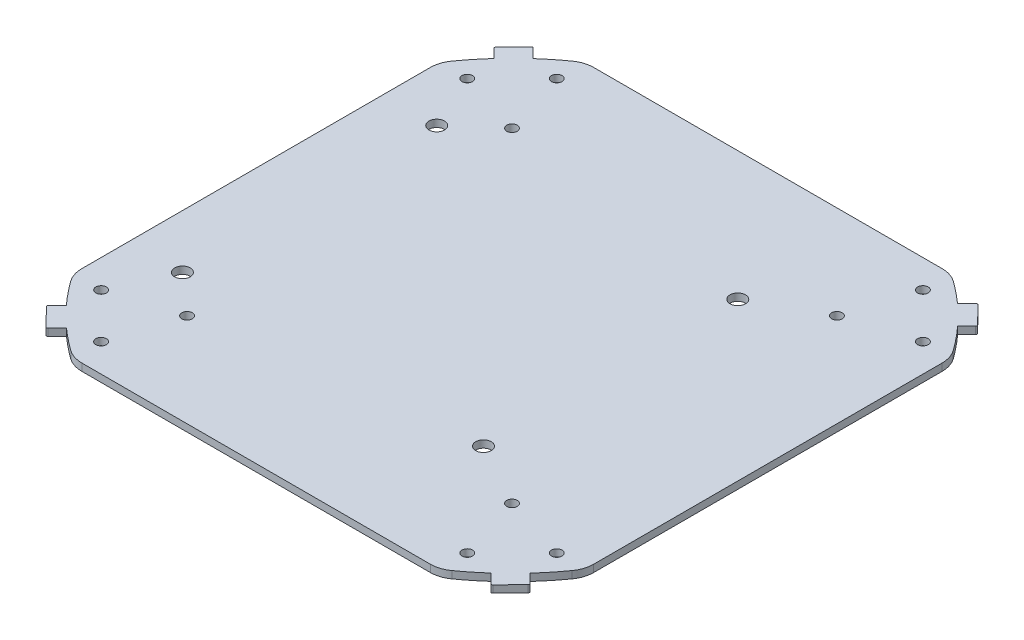
SolidWorks part; units mm, degrees
ref_plane "Front Plane" through (0, 0, 0) normal (0, 0, 1) x (1, 0, 0)
ref_plane "Top Plane" through (0, 0, 0) normal (0, 1, 0) x (1, 0, 0)
ref_plane "Right Plane" through (0, 0, 0) normal (1, 0, 0) x (0, 0, -1)
sketch "Sketch1" plane through (0, 0, 0) normal (0, 1, 0) x (1, 0, 0)
  line L0 (-1000, 0) -> (49000, 0) construction
  line L1 (0, -1000) -> (0, 49000) construction
  line L2 (707.1069, -707.1069) -> (-34648.2322, 34648.2322) construction
  line L3 (-707.1068, -707.1068) -> (34648.2323, 34648.2323) construction
  line L4 (716.0871, -698.1266) -> (0, 17.9605) construction
  line L5 (-698.1265, -716.087) -> (34657.2125, 34639.252) construction
  line L6 (698.1266, -716.0871) -> (-34657.2125, 34639.2519) construction
  line L7 (-716.087, -698.1265) -> (0, 17.9605) construction
  line L8 (-733.6258, -670.2105) -> (-31.7077, 31.7077) construction
  line L9 (733.9751, -670.5597) -> (22.7274, 40.6879) construction
  line L10 (39.5829, 36.115) -> (36.1358, 39.5583) construction
  line L11 (716.0871, -698.1266) -> (-34639.252, 34657.2125) construction
  line L12 (35.7817, 39.5534) -> (33.9856, 37.7573) construction
  line L13 (-716.087, -698.1265) -> (34639.252, 34657.2125) construction
  line L14 (39.5739, 35.7609) -> (37.7573, 33.9856) construction
  line L15 (39.5382, -36.1548) -> (36.0819, -39.6111) construction
  line L16 (39.5078, -35.8322) -> (37.7118, -34.0362) construction
  line L17 (-35.9968, -39.6764) -> (-39.3444, -36.2512) construction
  line L18 (-37.6038, -34.1555) -> (-39.3423, -35.894) construction
  line L19 (35.7129, -39.6171) -> (33.9376, -37.8006) construction
  line L20 (-35.6141, -39.7036) -> (-33.8181, -37.9075) construction
  line L21 (-39.7221, 35.8999) -> (-36.251, 39.2922) construction
  line L22 (-34.2033, 37.5603) -> (-35.8918, 39.2881) construction
  line L24 (-37.9528, 33.7672) -> (-39.7242, 35.5386) construction
  line L25 (-44.6575, -41.2092) -> (-46.396, -42.9477)
  line L26 (-43.0506, -46.7302) -> (-46.3981, -43.3049)
  line L27 (-42.6678, -46.7573) -> (-40.8718, -44.9612)
  line L28 (42.6678, -46.7573) -> (40.8718, -44.9612)
  line L29 (43.0506, -46.7302) -> (46.3981, -43.3049)
  line L30 (-39.4203, -35.9308) -> (-37.6038, -34.1555) [skipped]
  line L31 (-39.7488, 35.5633) -> (-37.9528, 33.7672) [skipped]
  line L32 (-35.9786, 39.3768) -> (-34.2033, 37.5603) [skipped]
  line L33 (44.6575, -41.2092) -> (46.396, -42.9477)
  line L35 (-44.6575, 41.2092) -> (-46.396, 42.9477)
  line L36 (-43.0506, 46.7302) -> (-46.3981, 43.3049)
  line L37 (-42.6678, 46.7573) -> (-40.8718, 44.9612)
  line L38 (44.6575, 41.2092) -> (46.396, 42.9477)
  line L39 (43.0506, 46.7302) -> (46.3981, 43.3049)
  line L40 (42.6678, 46.7573) -> (40.8718, 44.9612)
  line L43 (-33.5727, -49.3122) -> (33.5727, -49.3122)
  line L44 (49.3122, 33.5727) -> (49.3122, -33.5727)
  line L45 (33.5727, 49.3122) -> (-33.5727, 49.3122)
  line L46 (-49.3122, 33.5727) -> (-49.3122, -33.5727)
  arc A0 (-29.6486, 41.2505) -> (-34.2033, 37.5603) centre (0, 0) ccw construction
  arc A1 (-22.7274, 40.6879) -> (-29.6486, 41.2505) centre (-26.519, 36.8963) ccw construction
  arc A2 (-40.6879, 22.7274) -> (-41.2505, 29.6486) centre (-36.8963, 26.519) cw construction
  arc A3 (22.7274, 40.6879) -> (29.6486, 41.2505) centre (26.519, 36.8963) cw construction
  arc A4 (40.6879, 22.7274) -> (41.2505, 29.6486) centre (36.8963, 26.519) ccw construction
  arc A5 (40.6879, -22.7274) -> (41.2505, -29.6486) centre (36.8963, -26.519) cw construction
  arc A6 (22.7274, -40.6879) -> (29.6486, -41.2505) centre (26.519, -36.8963) ccw construction
  arc A7 (-22.7274, -40.6879) -> (-29.6486, -41.2505) centre (-26.519, -36.8963) cw construction
  arc A8 (-40.6879, -22.7274) -> (-41.2505, -29.6486) centre (-36.8963, -26.519) ccw construction
  arc A9 (-22.7274, 40.6879) -> (22.7274, 40.6879) centre (0, 66.2866) ccw construction
  arc A10 (40.6879, 22.7274) -> (40.6879, -22.7274) centre (66.2866, 0) ccw construction
  arc A11 (22.7274, -40.6879) -> (-22.7274, -40.6879) centre (0, -66.2866) ccw construction
  arc A12 (-40.6879, -22.7274) -> (-40.6879, 22.7274) centre (-66.2866, 0) ccw construction
  arc A13 (-29.6486, 41.2505) -> (-34.2033, 37.5603) centre (0, 0) ccw construction
  arc A14 (41.2505, 29.6486) -> (37.7573, 33.9856) centre (0, 0) ccw construction
  arc A15 (41.2505, 29.6486) -> (37.7573, 33.9856) centre (0, 0) ccw construction
  arc A16 (29.6486, -41.2505) -> (33.9376, -37.8006) centre (0, 0) ccw construction
  arc A17 (29.6486, -41.2505) -> (33.9376, -37.8006) centre (0, 0) ccw construction
  arc A18 (-41.2505, -29.6486) -> (-37.6038, -34.1555) centre (0, 0) ccw construction
  arc A19 (-41.2505, -29.6486) -> (-37.6038, -34.1555) centre (0, 0) ccw construction
  arc A20 (33.9856, 37.7573) -> (29.6486, 41.2505) centre (0, 0) ccw construction
  arc A21 (33.9856, 37.7573) -> (29.6486, 41.2505) centre (0, 0) ccw construction
  arc A22 (37.7118, -34.0362) -> (41.2505, -29.6486) centre (0, 0) ccw construction
  arc A23 (37.7118, -34.0362) -> (41.2505, -29.6486) centre (0, 0) ccw construction
  arc A24 (-33.8181, -37.9075) -> (-29.6486, -41.2505) centre (0, 0) ccw construction
  arc A25 (-33.8181, -37.9075) -> (-29.6486, -41.2505) centre (0, 0) ccw construction
  arc A26 (-37.9528, 33.7672) -> (-41.2505, 29.6486) centre (0, 0) ccw construction
  arc A27 (-37.9528, 33.7672) -> (-41.2505, 29.6486) centre (0, 0) ccw construction
  arc A28 (-35.6141, -39.7036) -> (-35.9968, -39.6764) centre (-35.7937, -39.5239) cw construction
  arc A29 (-39.3423, -35.894) -> (-39.3444, -36.2512) centre (-39.1627, -36.0736) ccw construction
  arc A30 (35.7129, -39.6171) -> (36.0819, -39.6111) centre (35.8945, -39.4396) ccw construction
  arc A31 (39.5078, -35.8322) -> (39.5382, -36.1548) centre (39.3282, -36.0118) cw construction
  arc A32 (39.5739, 35.7609) -> (39.5829, 36.115) centre (39.3964, 35.9426) ccw construction
  arc A33 (36.1358, 39.5583) -> (35.7817, 39.5534) centre (35.9613, 39.3738) ccw construction
  arc A34 (-39.7221, 35.8999) -> (-39.7242, 35.5386) centre (-39.5446, 35.7182) ccw construction
  arc A35 (-36.251, 39.2922) -> (-35.8918, 39.2881) centre (-36.0735, 39.1105) cw construction
  circle A36 centre (-28.2202, 36.8412) radius 1.016 construction
  circle A37 centre (-36.8412, 28.2202) radius 1.016 construction
  circle A38 centre (-24.2455, 24.2455) radius 1.016 construction
  circle A39 centre (28.2202, 36.8412) radius 1.016 construction
  circle A40 centre (36.8412, 28.2202) radius 1.016 construction
  circle A41 centre (24.2455, 24.2455) radius 1.016 construction
  circle A42 centre (36.8412, -28.2202) radius 1.016 construction
  circle A43 centre (28.2202, -36.8412) radius 1.016 construction
  circle A44 centre (24.2455, -24.2455) radius 1.016 construction
  circle A45 centre (-28.2202, -36.8412) radius 1.016 construction
  circle A46 centre (-36.8412, -28.2202) radius 1.016 construction
  circle A47 centre (-24.2455, -24.2455) radius 1.016 construction
  circle A48 centre (0, 0) radius 6.1441 construction
  arc A49 (-49.3122, -33.5727) -> (-48.3042, -36.7023) centre (-43.9501, -33.5727) ccw
  arc A50 (-48.3042, -36.7023) -> (-44.6575, -41.2092) centre (-7.0537, -7.0537) ccw
  arc A51 (-42.6678, -46.7573) -> (-43.0506, -46.7302) centre (-42.8474, -46.5777) cw
  arc A52 (-46.396, -42.9477) -> (-46.3981, -43.3049) centre (-46.2164, -43.1273) ccw
  arc A53 (-33.5727, -49.3122) -> (-36.7023, -48.3042) centre (-33.5727, -43.9501) cw
  arc A54 (-40.8718, -44.9612) -> (-36.7023, -48.3042) centre (-7.0537, -7.0537) ccw
  circle A55 centre (-35.2739, -43.8949) radius 1.016
  arc A56 (-40.8718, -44.9612) -> (-36.7023, -48.3042) centre (-7.0537, -7.0537) ccw construction
  circle A57 centre (-43.8949, -35.2739) radius 1.016
  circle A58 centre (-31.2992, -31.2992) radius 1.016
  arc A59 (42.6678, -46.7573) -> (43.0506, -46.7302) centre (42.8474, -46.5777) ccw
  arc A60 (46.396, -42.9477) -> (46.3981, -43.3049) centre (46.2164, -43.1273) cw
  circle A61 centre (43.8949, -35.2739) radius 1.016
  arc A62 (48.3042, -36.7023) -> (44.6575, -41.2092) centre (7.0537, -7.0537) cw
  arc A63 (49.3122, -33.5727) -> (48.3042, -36.7023) centre (43.9501, -33.5727) cw
  arc A64 (33.5727, -49.3122) -> (36.7023, -48.3042) centre (33.5727, -43.9501) ccw
  arc A65 (40.8718, -44.9612) -> (36.7023, -48.3042) centre (7.0537, -7.0537) cw
  circle A66 centre (35.2739, -43.8949) radius 1.016
  circle A67 centre (31.2992, -31.2992) radius 1.016
  arc A68 (-46.396, 42.9477) -> (-46.3981, 43.3049) centre (-46.2164, 43.1273) cw
  arc A69 (-42.6678, 46.7573) -> (-43.0506, 46.7302) centre (-42.8474, 46.5777) ccw
  arc A70 (-40.8718, 44.9612) -> (-36.7023, 48.3042) centre (-7.0537, 7.0537) cw
  arc A71 (-48.3042, 36.7023) -> (-44.6575, 41.2092) centre (-7.0537, 7.0537) cw
  arc A72 (-49.3122, 33.5727) -> (-48.3042, 36.7023) centre (-43.9501, 33.5727) cw
  arc A73 (-33.5727, 49.3122) -> (-36.7023, 48.3042) centre (-33.5727, 43.9501) ccw
  circle A74 centre (-35.2739, 43.8949) radius 1.016
  circle A75 centre (-31.2992, 31.2992) radius 1.016
  circle A76 centre (-43.8949, 35.2739) radius 1.016
  arc A77 (48.3042, 36.7023) -> (44.6575, 41.2092) centre (7.0537, 7.0537) ccw
  arc A78 (49.3122, 33.5727) -> (48.3042, 36.7023) centre (43.9501, 33.5727) ccw
  arc A79 (46.396, 42.9477) -> (46.3981, 43.3049) centre (46.2164, 43.1273) ccw
  arc A80 (42.6678, 46.7573) -> (43.0506, 46.7302) centre (42.8474, 46.5777) cw
  arc A81 (40.8718, 44.9612) -> (36.7023, 48.3042) centre (7.0537, 7.0537) ccw
  arc A82 (33.5727, 49.3122) -> (36.7023, 48.3042) centre (33.5727, 43.9501) cw
  circle A83 centre (43.8949, 35.2739) radius 1.016
  circle A84 centre (35.2739, 43.8949) radius 1.016
  circle A85 centre (31.2992, 31.2992) radius 1.016
  circle A90 centre (-39, 24.5) radius 1.5
  circle A91 centre (19, 24.5) radius 1.5
  circle A92 centre (19.003, -24.4994) radius 1.5
  circle A93 centre (-39, -24.5) radius 1.5
  point P46 (0, 0)
  point P60 (0, 0)
  point P75 (-0.0481, -0.2069)
  point P83 (41.6473, 37.8756)
  point P86 (37.8756, 41.6473)
  point P94 (-39, 24.5)
  point P120 (0, 0)
  point P208 (-39, -24.5)
  point P210 (19, 24.5)
  point P212 (19.003, -24.4994)
  dimension "D1" = 12.7
  dimension "D3" = 4
  dimension "D4" = 4
  dimension "D7" = 0.254
  dimension "D8" = 50.8
  dimension "D10" = 0.254
  dimension "D9" = 0.254
  dimension "D13" = 13.208
  dimension "D15" = 2
  dimension "D17" = 3
  dimension "D5" = 2.667
  dimension "D11" = 12.192
  dimension "D12" = 7.366
  dimension "D2" = 12.7
  dimension "D6" = 4
  dimension "D14" = 4
extrude "Boss-Extrude1" add sketch "Sketch1" along normal blind 1.397
